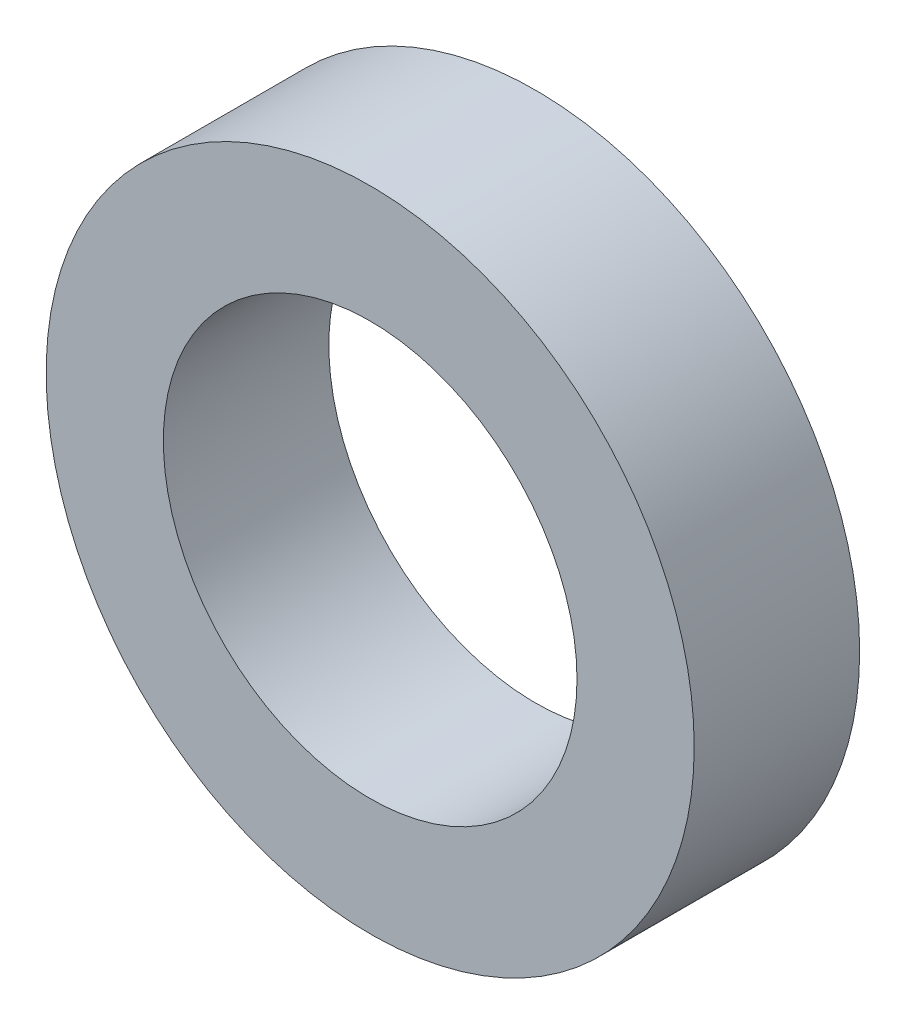
SolidWorks part; units mm, degrees
material "6061 合金"
ref_plane "前视基准面" through (0, 0, 0) normal (0, 0, 1) x (1, 0, 0)
ref_plane "上视基准面" through (0, 0, 0) normal (0, 1, 0) x (1, 0, 0)
ref_plane "右视基准面" through (0, 0, 0) normal (1, 0, 0) x (0, 0, -1)
other "Configuration Table"
sketch "草图1" plane through (0, 0, 0) normal (0, 0, 1) x (1, 0, 0)
  circle A0 centre (0, 0) radius 23.5
  circle A1 centre (0, 0) radius 15
  dimension "D1" = 30
  dimension "D2" = 47
extrude "凸台-拉伸1" add sketch "草图1" along normal blind 12
